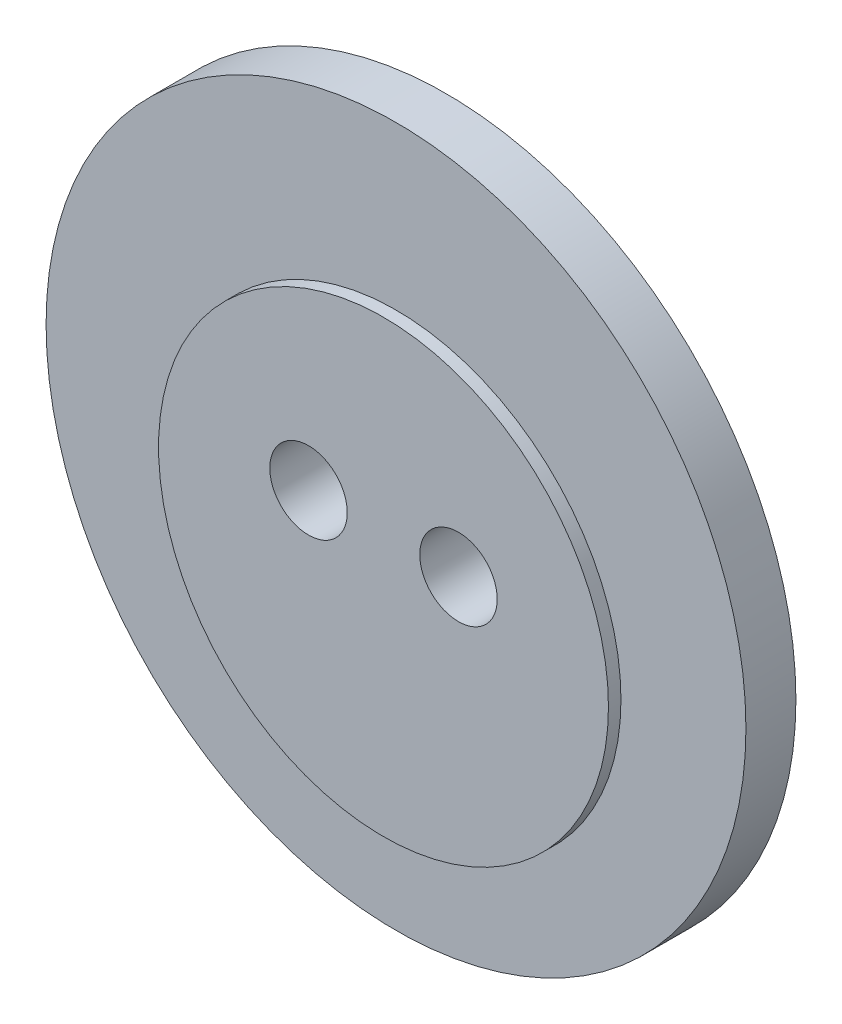
SolidWorks part; units mm, degrees
ref_plane "Front Plane" through (0, 0, 0) normal (0, 0, 1) x (1, 0, 0)
ref_plane "Top Plane" through (0, 0, 0) normal (0, 1, 0) x (1, 0, 0)
ref_plane "Right Plane" through (0, 0, 0) normal (1, 0, 0) x (0, 0, -1)
sketch "Sketch1" plane through (0, 0, 0) normal (0, 0, 1) x (1, 0, 0)
  circle A0 centre (0, 0) radius 14
  dimension "D1" = 28
extrude "Boss-Extrude1" add sketch "Sketch1" along normal blind 2
sketch "Sketch2" plane through (0, 0, 2) normal (0, 0, 1) x (1, 0, 0)
  line L0 (0, 14.3027) -> (0, -14.8918) construction
  circle A0 centre (0, -1.5) radius 9
  dimension "D1" = 18
  dimension "D2" = 1.5
extrude "Boss-Extrude2" add sketch "Sketch2" along normal blind 0.5
sketch "Sketch6" plane through (0, 0, 0) normal (0, 0, -1) x (-1, 0, 0)
  line L0 (0, 14.5318) -> (0, -15.3828) construction
  circle A0 centre (0, 1.5) radius 9
  dimension "D1" = 18
  dimension "D2" = 1.5
extrude "Boss-Extrude4" add sketch "Sketch6" along normal blind 0.5
sketch "Sketch7" plane through (0, 0, 2.5) normal (0, 0, 1) x (1, 0, 0)
  line L0 (-15.481, 0) -> (17.1829, 0) construction
  line L1 (0, -14.7282) -> (0, 14.27) construction
  circle A0 centre (3, 0) radius 1.55
  circle A1 centre (-3, 0) radius 1.55
  dimension "D1" = 3.1
  dimension "D2" = 3
extrude "Cut-Extrude1" cut sketch "Sketch7" against normal through all
